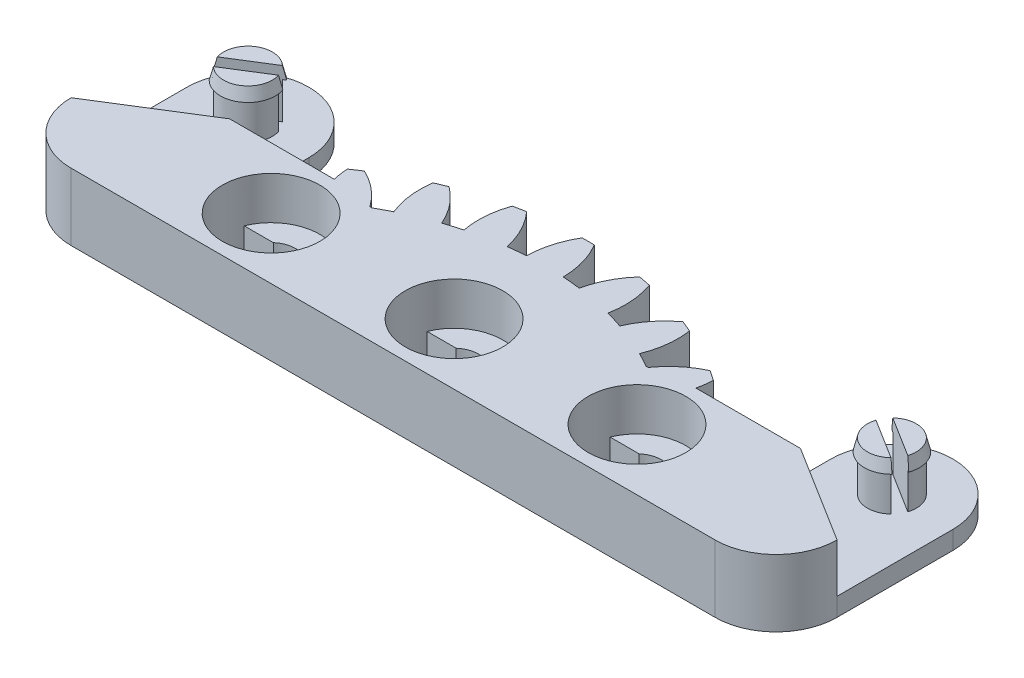
SolidWorks part; units mm, degrees
ref_plane "前视基准面" through (0, 0, 0) normal (0, 0, 1) x (1, 0, 0)
ref_plane "上视基准面" through (0, 0, 0) normal (0, 1, 0) x (1, 0, 0)
ref_plane "右视基准面" through (0, 0, 0) normal (1, 0, 0) x (0, 0, -1)
sketch "草图1" plane through (0, 0, 0) normal (0, 1, 0) x (1, 0, 0)
  line L0 (0, 0) -> (0, -5) construction
  line L1 (-26.4, -5) -> (26.4, -5)
  line L2 (31.4, 0) -> (31.4, 9.5)
  line L3 (31.4, 9.5) -> (26.4, 9.5) construction
  line L4 (21.4, 9.5) -> (21.4, 5)
  line L5 (0, 0) -> (0, 7.5) construction
  line L6 (-11.25, 7.5) -> (11.25, 7.5) construction
  line L7 (11.25, 7.5) -> (11.25, 4.5) construction
  line L8 (21.4, 5) -> (14.9, 5)
  line L9 (11.25, 4.5) -> (14.9, 5)
  line L10 (-31.4, 0) -> (-31.4, 9.5)
  line L11 (-21.4, 9.5) -> (-21.4, 5)
  line L12 (-21.4, 5) -> (-14.9, 5)
  line L13 (-11.25, 4.5) -> (-14.9, 5)
  line L14 (-11.25, 7.5) -> (-11.25, 4.5) construction
  arc A0 (31.4, 9.5) -> (21.4, 9.5) centre (26.4, 9.5) ccw
  arc A1 (26.4, -5) -> (31.4, 0) centre (26.4, 0) ccw
  arc A2 (-26.4, -5) -> (-31.4, 0) centre (-26.4, 0) cw
  arc A3 (-31.4, 9.5) -> (-21.4, 9.5) centre (-26.4, 9.5) cw
  arc A4 (-11.25, 4.5) -> (11.25, 4.5) centre (0, -15.0937) cw
  point P10 (31.4, -5)
  dimension "D6" = 5
  dimension "D1" = 5
  dimension "D2" = 31.4
  dimension "D3" = 14.5
  dimension "D4" = 5
  dimension "D5" = 4.5
  dimension "D7" = 7.5
  dimension "D8" = 11.25
  dimension "D9" = 3
  dimension "D10" = 6.5
extrude "凸台-拉伸1" add sketch "草图1" along normal blind 1.5
sketch "草图2" plane through (0, 1.5, 0) normal (0, 1, 0) x (1, 0, 0)
  line L0 (-21.4, 5) -> (-23.4, 5)
  line L1 (-23.4, 5) -> (-31.4, 0)
  line L2 (21.4, 5) -> (23.4, 5)
  line L3 (23.4, 5) -> (31.4, 0)
  line L9 (31.4, 0) -> (31.4, 9.5)
  line L10 (21.4, 9.5) -> (21.4, 5)
  line L11 (21.4, 5) -> (14.9, 5)
  line L12 (14.9, 5) -> (11.25, 4.5)
  line L13 (-11.25, 4.5) -> (-14.9, 5)
  line L14 (-14.9, 5) -> (-21.4, 5)
  line L15 (-21.4, 5) -> (-21.4, 9.5)
  line L16 (-31.4, 9.5) -> (-31.4, 0)
  line L17 (-26.4, -5) -> (26.4, -5)
  line L20 (21.4, 5) -> (14.9, 5)
  line L21 (14.9, 5) -> (11.25, 4.5)
  line L22 (-11.25, 4.5) -> (-14.9, 5)
  line L23 (-14.9, 5) -> (-21.4, 5)
  line L26 (-26.4, -5) -> (26.4, -5)
  arc A5 (26.4, -5) -> (31.4, 0) centre (26.4, 0) ccw
  arc A6 (31.4, 9.5) -> (21.4, 9.5) centre (26.4, 9.5) ccw
  arc A7 (11.25, 4.5) -> (-11.25, 4.5) centre (0, -15.0937) ccw
  arc A8 (-21.4, 9.5) -> (-31.4, 9.5) centre (-26.4, 9.5) ccw
  arc A9 (-31.4, 0) -> (-26.4, -5) centre (-26.4, 0) ccw
  arc A10 (26.4, -5) -> (31.4, 0) centre (26.4, 0) ccw
  arc A12 (11.25, 4.5) -> (-11.25, 4.5) centre (0, -15.0937) ccw
  arc A14 (-31.4, 0) -> (-26.4, -5) centre (-26.4, 0) ccw
  dimension "D2" = 2
  dimension "D3" = 2
  dimension "D1" = 0
extrude "凸台-拉伸2" add sketch "草图2" along normal blind 4
sketch "草图3" plane through (0, 0, 0) normal (0, 1, 0) x (1, 0, 0)
  line L0 (0, 0) -> (0, 7.5) construction
  line L1 (0, 7.5) -> (0, 11) construction
  line L2 (0.5, 11) -> (-0.5, 11)
  line L3 (0, 9.25) -> (-1.25, 9.25) construction
  line L4 (0, 7.5) -> (-1.5, 7.5) construction
  arc A0 (11.25, 4.5) -> (-11.25, 4.5) centre (0, -15.0937) ccw construction
  arc A1 (1.5006, 7.4501) -> (-1.5006, 7.4501) centre (0, -15.0937) ccw
  arc A2 (-0.5, 11) -> (-1.5006, 7.4501) centre (5.5, 7.3929) ccw
  arc A3 (0.5, 11) -> (1.5006, 7.4501) centre (-5.5, 7.3929) cw
  dimension "D1" = 0.5
  dimension "D2" = 1.25
  dimension "D3" = 1.5
  dimension "D4" = 3.5
extrude "凸台-拉伸3" add sketch "草图3" along normal blind 5.5
pattern_circular "阵列(圆周)1" count 4 over 34 about axis through (0, 0, 15.0937) along (0, 1, 0) of "凸台-拉伸3"
pattern_circular "阵列(圆周)2" count 4 over 34 about axis through (0, 0, 15.0937) along (0, 1, 0) of "阵列(圆周)1"
sketch "草图4" plane through (0, 5.5, 0) normal (0, 1, 0) x (1, 0, 0)
  circle A0 centre (0, 0) radius 4
  dimension "D1" = 8
extrude "切除-拉伸1" cut sketch "草图4" against normal blind 3.5
sketch "草图5" plane through (0, 2, 0) normal (0, 1, 0) x (1, 0, 0)
  line L0 (0, 0) -> (0, 1.5) construction
  line L1 (-1.3229, 1.5) -> (-3.7081, 1.5)
  line L2 (0, 0) -> (0, -1.5) construction
  line L3 (-1.3229, -1.5) -> (-3.7081, -1.5)
  line L4 (1.3229, -1.5) -> (3.7081, -1.5)
  line L5 (1.3229, 1.5) -> (3.7081, 1.5)
  arc A0 (-1.3229, -1.5) -> (1.3229, -1.5) centre (0, 0) ccw
  arc A1 (-3.7081, 1.5) -> (-3.7081, -1.5) centre (0, 0) ccw
  arc A2 (3.7081, 1.5) -> (3.7081, -1.5) centre (0, 0) cw
  arc A3 (1.3229, 1.5) -> (-1.3229, 1.5) centre (0, 0) ccw
  dimension "D1" = 4
  dimension "D2" = 8
  dimension "D3" = 1.5
  dimension "D4" = 1.5
  dimension "D5" = 1.3229
  dimension "D6" = 1.3229
extrude "切除-拉伸2" cut sketch "草图5" against normal through all
pattern_linear "阵列(线性)1" count 2 spacing 15 along (-1, 0, 0) count 2 spacing 15 along (1, 0, 0) of "切除-拉伸1", "切除-拉伸2"
sketch "草图6" plane through (0, 1.5, 0) normal (0, 1, 0) x (1, 0, 0)
  circle A0 centre (-26.4, 9.5) radius 2
  arc A1 (-21.4, 9.5) -> (-31.4, 9.5) centre (-26.4, 9.5) ccw construction
  point P0 (-26.4, 14.5)
  dimension "D2" = 4
  dimension "D1" = 5
  dimension "D3" = 5
extrude "凸台-拉伸4" add sketch "草图6" along normal blind 4
ref_plane "基准面1" through (0, 4.5, 0) normal (0, 1, 0) x (1, 0, 0)
sketch "草图7" plane through (0, 4.5, 0) normal (0, 1, 0) x (1, 0, 0)
  circle A0 centre (-26.4, 9.5) radius 2.25
  dimension "D1" = 4.5
sketch "草图8" plane through (0, 5.5, 0) normal (0, 1, 0) x (1, 0, 0)
  circle A0 centre (-26.4, 9.5) radius 2
  dimension "D1" = 4
loft "放样1" add profiles "草图8", "草图7"
sketch "草图9" plane through (0, 5.5, 0) normal (0, 1, 0) x (1, 0, 0)
  line L0 (-26.4, 9.5) -> (-22.103, 2.6248) construction
  line L1 (-28.944, 7.91) -> (-23.856, 11.09) construction
  line L2 (-28.679, 7.486) -> (-23.591, 10.666)
  line L3 (-29.209, 8.334) -> (-24.121, 11.514)
  line L4 (-29.209, 8.334) -> (-28.679, 7.486)
  line L5 (-24.121, 11.514) -> (-23.591, 10.666)
  dimension "D1" = 6
  dimension "D2" = 0.5
  dimension "D3" = 0.5
extrude "切除-拉伸3" cut sketch "草图9" against normal blind 4
mirror "镜向1" about plane through (0, 0, 0) normal (1, 0, 0) of "切除-拉伸3", "放样1", "凸台-拉伸4"
